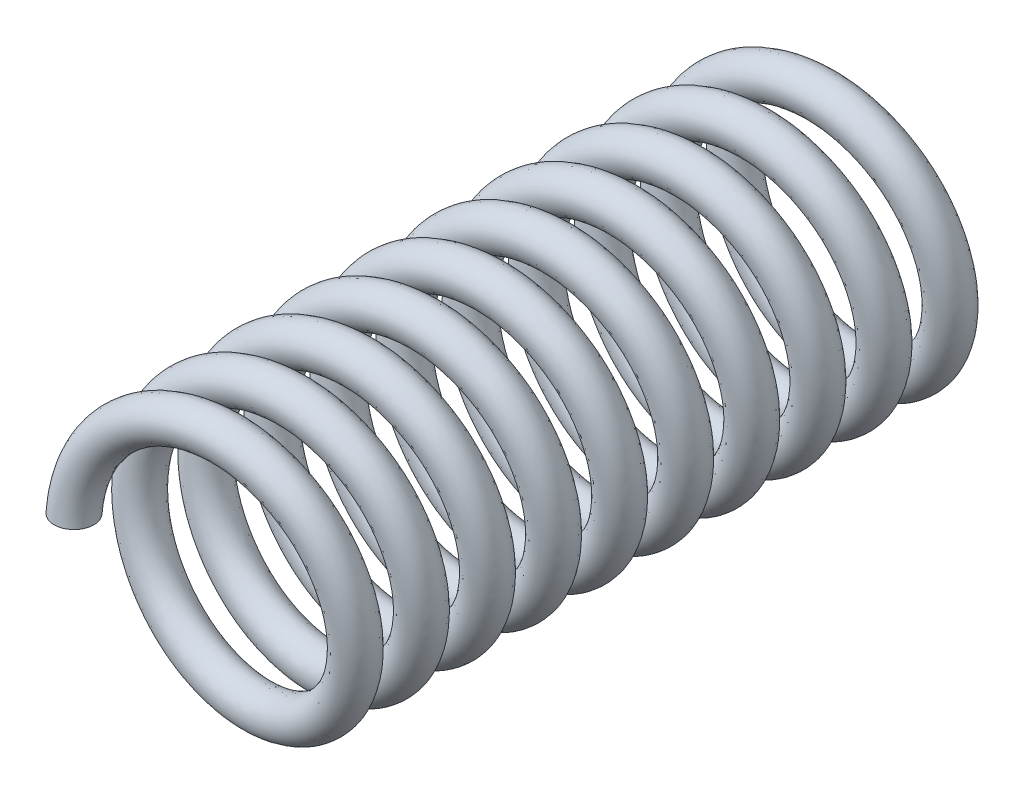
SolidWorks part; units mm, degrees
ref_plane "Front Plane" through (0, 0, 0) normal (0, 0, 1) x (1, 0, 0)
ref_plane "Top Plane" through (0, 0, 0) normal (0, 1, 0) x (1, 0, 0)
ref_plane "Right Plane" through (0, 0, 0) normal (1, 0, 0) x (0, 0, -1)
sketch "Sketch1" plane through (0, 0, 0) normal (0, 0, 1) x (1, 0, 0)
  circle A0 centre (0, 0) radius 3.75
  dimension "D1" = 7.5
curve "Helix/Spiral1" pitch 2 height 20 turns 10
sketch "Sketch3" plane through (0, 0, 0) normal (0, 1, 0) x (1, 0, 0)
  circle A0 centre (-3.75, 0) radius 0.6
  spline S0 degree 3 poles (-3.75, 0) (-3.75, -0.0414) (-3.5547, -0.1251) (-2.7207, -0.25) (-1.4724, -0.375) (0, -0.5) (1.4724, -0.625) (2.7207, -0.75) (3.5547, -0.875) (3.8476, -1) (3.5547, -1.125) (2.7207, -1.25) (1.4724, -1.375) (0, -1.5) (-1.4724, -1.625) (-2.7207, -1.75) (-3.5547, -1.875) (-3.8476, -2) (-3.5547, -2.125) (-2.7207, -2.25) (-1.4724, -2.375) (0, -2.5) (1.4724, -2.625) (2.7207, -2.75) (3.5547, -2.875) (3.8476, -3) (3.5547, -3.125) (2.7207, -3.25) (1.4724, -3.375) (0, -3.5) (-1.4724, -3.625) (-2.7207, -3.75) (-3.5547, -3.875) (-3.8476, -4) (-3.5547, -4.125) (-2.7207, -4.25) (-1.4724, -4.375) (0, -4.5) (1.4724, -4.625) (2.7207, -4.75) (3.5547, -4.875) (3.8476, -5) (3.5547, -5.125) (2.7207, -5.25) (1.4724, -5.375) (0, -5.5) (-1.4724, -5.625) (-2.7207, -5.75) (-3.5547, -5.875) (-3.8476, -6) (-3.5547, -6.125) (-2.7207, -6.25) (-1.4724, -6.375) (0, -6.5) (1.4724, -6.625) (2.7207, -6.75) (3.5547, -6.875) (3.8476, -7) (3.5547, -7.125) (2.7207, -7.25) (1.4724, -7.375) (0, -7.5) (-1.4724, -7.625) (-2.7207, -7.75) (-3.5547, -7.875) (-3.8476, -8) (-3.5547, -8.125) (-2.7207, -8.25) (-1.4724, -8.375) (0, -8.5) (1.4724, -8.625) (2.7207, -8.75) (3.5547, -8.875) (3.8476, -9) (3.5547, -9.125) (2.7207, -9.25) (1.4724, -9.375) (0, -9.5) (-1.4724, -9.625) (-2.7207, -9.75) (-3.5547, -9.875) (-3.8476, -10) (-3.5547, -10.125) (-2.7207, -10.25) (-1.4724, -10.375) (0, -10.5) (1.4724, -10.625) (2.7207, -10.75) (3.5547, -10.875) (3.8476, -11) (3.5547, -11.125) (2.7207, -11.25) (1.4724, -11.375) (0, -11.5) (-1.4724, -11.625) (-2.7207, -11.75) (-3.5547, -11.875) (-3.8476, -12) (-3.5547, -12.125) (-2.7207, -12.25) (-1.4724, -12.375) (0, -12.5) (1.4724, -12.625) (2.7207, -12.75) (3.5547, -12.875) (3.8476, -13) (3.5547, -13.125) (2.7207, -13.25) (1.4724, -13.375) (0, -13.5) (-1.4724, -13.625) (-2.7207, -13.75) (-3.5547, -13.875) (-3.8476, -14) (-3.5547, -14.125) (-2.7207, -14.25) (-1.4724, -14.375) (0, -14.5) (1.4724, -14.625) (2.7207, -14.75) (3.5547, -14.875) (3.8476, -15) (3.5547, -15.125) (2.7207, -15.25) (1.4724, -15.375) (0, -15.5) (-1.4724, -15.625) (-2.7207, -15.75) (-3.5547, -15.875) (-3.8476, -16) (-3.5547, -16.125) (-2.7207, -16.25) (-1.4724, -16.375) (0, -16.5) (1.4724, -16.625) (2.7207, -16.75) (3.5547, -16.875) (3.8476, -17) (3.5547, -17.125) (2.7207, -17.25) (1.4724, -17.375) (0, -17.5) (-1.4724, -17.625) (-2.7207, -17.75) (-3.5547, -17.875) (-3.8476, -18) (-3.5547, -18.125) (-2.7207, -18.25) (-1.4724, -18.375) (0, -18.5) (1.4724, -18.625) (2.7207, -18.75) (3.5547, -18.875) (3.8476, -19) (3.5547, -19.125) (2.7207, -19.25) (1.4724, -19.375) (0, -19.5) (-1.4724, -19.625) (-2.7207, -19.75) (-3.5547, -19.8749) (-3.75, -19.9586) (-3.75, -20) knots 0 0 0 0 0.00625 0.0125 0.01875 0.025 0.03125 0.0375 0.04375 0.05 0.05625 0.0625 0.06875 0.075 0.08125 0.0875 0.09375 0.1 0.10625 0.1125 0.11875 0.125 0.13125 0.1375 0.14375 0.15 0.15625 0.1625 0.16875 0.175 0.18125 0.1875 0.19375 0.2 0.20625 0.2125 0.21875 0.225 0.23125 0.2375 0.24375 0.25 0.25625 0.2625 0.26875 0.275 0.28125 0.2875 0.29375 0.3 0.30625 0.3125 0.31875 0.325 0.33125 0.3375 0.34375 0.35 0.35625 0.3625 0.36875 0.375 0.38125 0.3875 0.39375 0.4 0.40625 0.4125 0.41875 0.425 0.43125 0.4375 0.44375 0.45 0.45625 0.4625 0.46875 0.475 0.48125 0.4875 0.49375 0.5 0.50625 0.5125 0.51875 0.525 0.53125 0.5375 0.54375 0.55 0.55625 0.5625 0.56875 0.575 0.58125 0.5875 0.59375 0.6 0.60625 0.6125 0.61875 0.625 0.63125 0.6375 0.64375 0.65 0.65625 0.6625 0.66875 0.675 0.68125 0.6875 0.69375 0.7 0.70625 0.7125 0.71875 0.725 0.73125 0.7375 0.74375 0.75 0.75625 0.7625 0.76875 0.775 0.78125 0.7875 0.79375 0.8 0.80625 0.8125 0.81875 0.825 0.83125 0.8375 0.84375 0.85 0.85625 0.8625 0.86875 0.875 0.88125 0.8875 0.89375 0.9 0.90625 0.9125 0.91875 0.925 0.93125 0.9375 0.94375 0.95 0.95625 0.9625 0.96875 0.975 0.98125 0.9875 0.99375 1 1 1 1 construction
  dimension "D1" = 1.2
sweep "Sweep1" add profiles "Sketch3" path "Helix/Spiral1"
